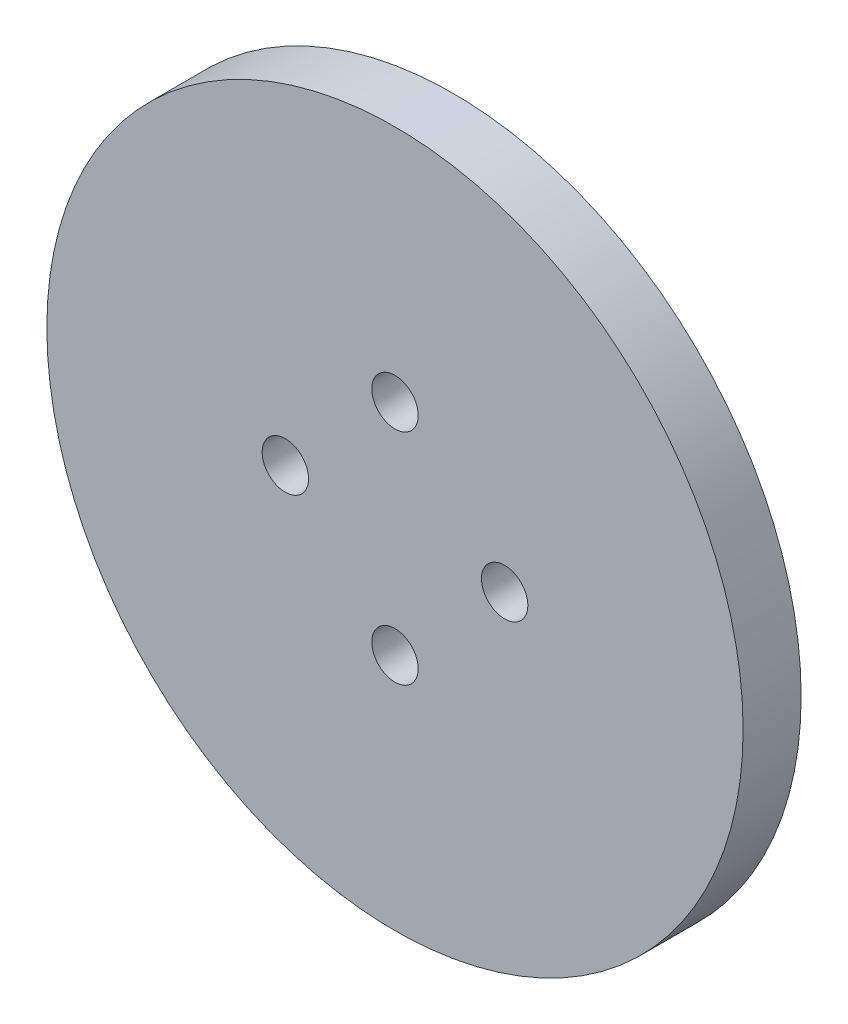
SolidWorks part; units mm, degrees
ref_plane "Front Plane" through (0, 0, 0) normal (0, 0, 1) x (1, 0, 0)
ref_plane "Top Plane" through (0, 0, 0) normal (0, 1, 0) x (1, 0, 0)
ref_plane "Right Plane" through (0, 0, 0) normal (1, 0, 0) x (0, 0, -1)
sketch "Sketch1" plane through (0, 0, 0) normal (0, 0, 1) x (1, 0, 0)
  circle A0 centre (0, 0) radius 38.1
  circle A1 centre (12, 0) radius 2.54
  circle A2 centre (0, -12) radius 2.54
  circle A3 centre (-12, 0) radius 2.54
  circle A4 centre (0, 12) radius 2.54
  point P5 (-1.7053, -13.9535)
  point P14 (0, 0)
  dimension "D1" = 76.2
  dimension "D2" = 5.08
  dimension "D3" = 12
  dimension "D4" = 4
extrude "Boss-Extrude1" add sketch "Sketch1" along normal blind 6.35
